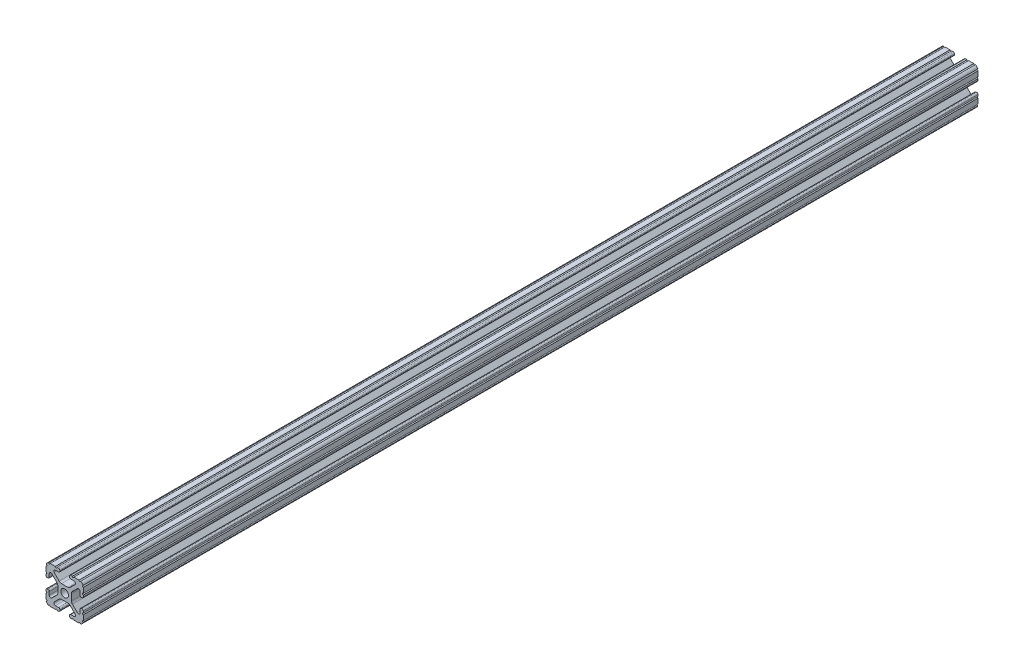
SolidWorks part; units mm, degrees
ref_plane "Front Plane" through (0, 0, 0) normal (0, 0, 1) x (1, 0, 0)
ref_plane "Top Plane" through (0, 0, 0) normal (0, 1, 0) x (1, 0, 0)
ref_plane "Right Plane" through (0, 0, 0) normal (1, 0, 0) x (0, 0, -1)
sketch "Sketch1" plane through (0, 0, 0) normal (0, 0, 1) x (1, 0, 0)
  line L0 (-3.7373, -5.2999) -> (-7.1039, -8.6665)
  line L1 (-6.3485, -10.4902) -> (-4.1904, -10.4902)
  line L2 (-3.2512, -11.4294) -> (-3.2512, -11.7608)
  line L3 (-4.1904, -12.7) -> (-5.2436, -12.7)
  line L4 (-6.3485, -12.7) -> (-9.8037, -12.7)
  line L5 (-12.7, -9.8037) -> (-12.7, -6.3485)
  line L6 (-12.7, -5.2436) -> (-12.7, -4.1904)
  line L7 (-11.7608, -3.2512) -> (-11.4294, -3.2512)
  line L8 (-10.4902, -4.1904) -> (-10.4902, -6.3485)
  line L9 (-8.6665, -7.1039) -> (-5.2999, -3.7373)
  line L10 (-4.6482, -2.164) -> (-4.6482, 2.164)
  line L11 (-8.6665, 7.1039) -> (-5.2999, 3.7373)
  line L12 (-10.4902, 4.1904) -> (-10.4902, 6.3485)
  line L13 (-11.7608, 3.2512) -> (-11.4294, 3.2512)
  line L14 (-12.7, 5.2436) -> (-12.7, 4.1904)
  line L15 (-12.7, 9.8037) -> (-12.7, 6.3485)
  line L16 (-6.3485, 12.7) -> (-9.8037, 12.7)
  line L17 (-4.1904, 12.7) -> (-5.2436, 12.7)
  line L18 (-3.2512, 11.4294) -> (-3.2512, 11.7608)
  line L19 (-6.3485, 10.4902) -> (-4.1904, 10.4902)
  line L20 (-3.7373, 5.2999) -> (-7.1039, 8.6665)
  line L21 (-2.164, 4.6482) -> (2.164, 4.6482)
  line L22 (3.7373, 5.2999) -> (7.1039, 8.6665)
  line L23 (6.3485, 10.4902) -> (4.1904, 10.4902)
  line L24 (3.2512, 11.4294) -> (3.2512, 11.7608)
  line L25 (4.1904, 12.7) -> (5.2436, 12.7)
  line L26 (6.3485, 12.7) -> (9.8037, 12.7)
  line L27 (12.7, 9.8037) -> (12.7, 6.3485)
  line L28 (12.7, 5.2436) -> (12.7, 4.1904)
  line L29 (11.7608, 3.2512) -> (11.4294, 3.2512)
  line L30 (10.4902, 4.1904) -> (10.4902, 6.3485)
  line L31 (8.6665, 7.1039) -> (5.2999, 3.7373)
  line L32 (3.2512, -11.4294) -> (3.2512, -11.7608)
  line L33 (6.3485, -10.4902) -> (4.1904, -10.4902)
  line L34 (3.7373, -5.2999) -> (7.1039, -8.6665)
  line L35 (-2.164, -4.6482) -> (2.164, -4.6482)
  line L36 (4.6482, -2.164) -> (4.6482, 2.164)
  line L37 (8.6665, -7.1039) -> (5.2999, -3.7373)
  line L38 (10.4902, -4.1904) -> (10.4902, -6.3485)
  line L39 (11.7608, -3.2512) -> (11.4294, -3.2512)
  line L40 (12.7, -5.2436) -> (12.7, -4.1904)
  line L41 (6.3485, -12.7) -> (9.8037, -12.7)
  line L42 (12.7, -9.8037) -> (12.7, -6.3485)
  line L43 (4.1904, -12.7) -> (5.2436, -12.7)
  circle A0 centre (0, 0) radius 2.6035
  arc A1 (12.7, -9.8037) -> (12.58, -10.8954) centre (12.7, -10.3562) ccw
  arc A2 (10.8954, -12.58) -> (9.8037, -12.7) centre (10.3562, -12.7) ccw
  arc A3 (6.3485, -12.7) -> (5.2436, -12.7) centre (5.796, -12.7) ccw
  arc A4 (-2.164, -4.6482) -> (-3.7373, -5.2999) centre (-2.164, -6.8732) ccw
  arc A5 (-7.1039, -8.6665) -> (-6.3485, -10.4902) centre (-6.3485, -9.4219) ccw
  arc A6 (-3.2512, -11.4294) -> (-4.1904, -10.4902) centre (-4.1904, -11.4294) ccw
  arc A7 (-4.1904, -12.7) -> (-3.2512, -11.7608) centre (-4.1904, -11.7608) ccw
  arc A8 (-5.2436, -12.7) -> (-6.3485, -12.7) centre (-5.796, -12.7) ccw
  arc A9 (-9.8037, -12.7) -> (-10.8954, -12.58) centre (-10.3562, -12.7) ccw
  arc A10 (-12.58, -10.8954) -> (-10.8954, -12.58) centre (-10.1173, -10.1173) ccw
  arc A11 (-12.58, -10.8954) -> (-12.7, -9.8037) centre (-12.7, -10.3562) ccw
  arc A12 (-12.7, -6.3485) -> (-12.7, -5.2436) centre (-12.7, -5.796) ccw
  arc A13 (-11.7608, -3.2512) -> (-12.7, -4.1904) centre (-11.7608, -4.1904) ccw
  arc A14 (-10.4902, -4.1904) -> (-11.4294, -3.2512) centre (-11.4294, -4.1904) ccw
  arc A15 (-10.4902, -6.3485) -> (-8.6665, -7.1039) centre (-9.4219, -6.3485) ccw
  arc A16 (-5.2999, -3.7373) -> (-4.6482, -2.164) centre (-6.8732, -2.164) ccw
  arc A17 (-4.6482, 2.164) -> (-5.2999, 3.7373) centre (-6.8732, 2.164) ccw
  arc A18 (-8.6665, 7.1039) -> (-10.4902, 6.3485) centre (-9.4219, 6.3485) ccw
  arc A19 (-11.4294, 3.2512) -> (-10.4902, 4.1904) centre (-11.4294, 4.1904) ccw
  arc A20 (-12.7, 4.1904) -> (-11.7608, 3.2512) centre (-11.7608, 4.1904) ccw
  arc A21 (-12.7, 5.2436) -> (-12.7, 6.3485) centre (-12.7, 5.796) ccw
  arc A22 (-12.7, 9.8037) -> (-12.58, 10.8954) centre (-12.7, 10.3562) ccw
  arc A23 (-10.8954, 12.58) -> (-12.58, 10.8954) centre (-10.1173, 10.1173) ccw
  arc A24 (-10.8954, 12.58) -> (-9.8037, 12.7) centre (-10.3562, 12.7) ccw
  arc A25 (-6.3485, 12.7) -> (-5.2436, 12.7) centre (-5.796, 12.7) ccw
  arc A26 (-3.2512, 11.7608) -> (-4.1904, 12.7) centre (-4.1904, 11.7608) ccw
  arc A27 (-4.1904, 10.4902) -> (-3.2512, 11.4294) centre (-4.1904, 11.4294) ccw
  arc A28 (-6.3485, 10.4902) -> (-7.1039, 8.6665) centre (-6.3485, 9.4219) ccw
  arc A29 (-3.7373, 5.2999) -> (-2.164, 4.6482) centre (-2.164, 6.8732) ccw
  arc A30 (2.164, 4.6482) -> (3.7373, 5.2999) centre (2.164, 6.8732) ccw
  arc A31 (7.1039, 8.6665) -> (6.3485, 10.4902) centre (6.3485, 9.4219) ccw
  arc A32 (3.2512, 11.4294) -> (4.1904, 10.4902) centre (4.1904, 11.4294) ccw
  arc A33 (4.1904, 12.7) -> (3.2512, 11.7608) centre (4.1904, 11.7608) ccw
  arc A34 (5.2436, 12.7) -> (6.3485, 12.7) centre (5.796, 12.7) ccw
  arc A35 (9.8037, 12.7) -> (10.8954, 12.58) centre (10.3562, 12.7) ccw
  arc A36 (12.58, 10.8954) -> (10.8954, 12.58) centre (10.1173, 10.1173) ccw
  arc A37 (12.58, 10.8954) -> (12.7, 9.8037) centre (12.7, 10.3562) ccw
  arc A38 (12.7, 6.3485) -> (12.7, 5.2436) centre (12.7, 5.796) ccw
  arc A39 (11.7608, 3.2512) -> (12.7, 4.1904) centre (11.7608, 4.1904) ccw
  arc A40 (10.4902, 4.1904) -> (11.4294, 3.2512) centre (11.4294, 4.1904) ccw
  arc A41 (10.4902, 6.3485) -> (8.6665, 7.1039) centre (9.4219, 6.3485) ccw
  arc A42 (5.2999, 3.7373) -> (4.6482, 2.164) centre (6.8732, 2.164) ccw
  arc A43 (12.7, -5.2436) -> (12.7, -6.3485) centre (12.7, -5.796) ccw
  arc A44 (4.1904, -10.4902) -> (3.2512, -11.4294) centre (4.1904, -11.4294) ccw
  arc A45 (6.3485, -10.4902) -> (7.1039, -8.6665) centre (6.3485, -9.4219) ccw
  arc A46 (3.7373, -5.2999) -> (2.164, -4.6482) centre (2.164, -6.8732) ccw
  arc A47 (4.6482, -2.164) -> (5.2999, -3.7373) centre (6.8732, -2.164) ccw
  arc A48 (8.6665, -7.1039) -> (10.4902, -6.3485) centre (9.4219, -6.3485) ccw
  arc A49 (11.4294, -3.2512) -> (10.4902, -4.1904) centre (11.4294, -4.1904) ccw
  arc A50 (12.7, -4.1904) -> (11.7608, -3.2512) centre (11.7608, -4.1904) ccw
  arc A51 (10.8954, -12.58) -> (12.58, -10.8954) centre (10.1173, -10.1173) ccw
  arc A52 (3.2512, -11.7608) -> (4.1904, -12.7) centre (4.1904, -11.7608) ccw
extrude "Boss-Extrude1" add sketch "Sketch1" along normal blind 609.6
